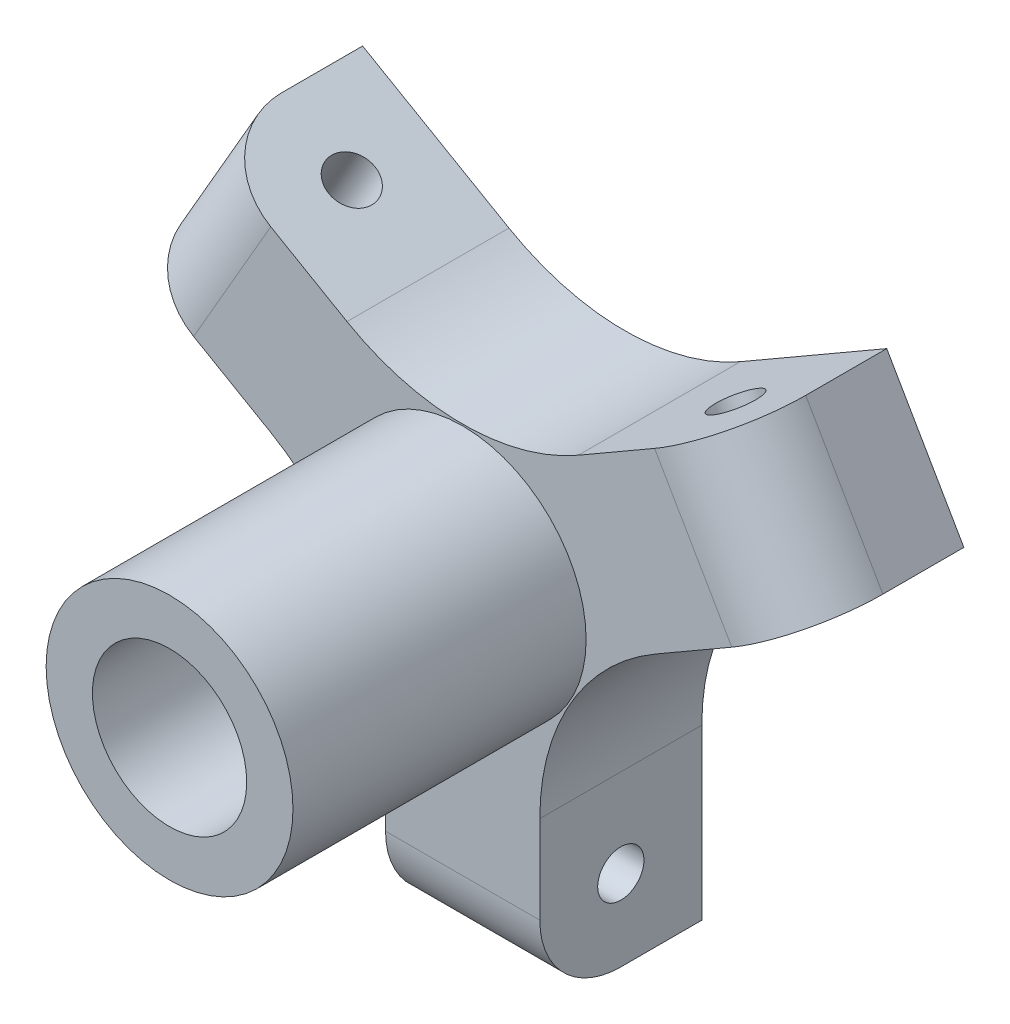
SolidWorks part; units mm, degrees
material "Hierro dúctil (SN)"
ref_plane "Alzado" through (0, 0, 0) normal (0, 0, 1) x (1, 0, 0)
ref_plane "Planta" through (0, 0, 0) normal (0, 1, 0) x (1, 0, 0)
ref_plane "Vista lateral" through (0, 0, 0) normal (1, 0, 0) x (0, 0, -1)
sketch "Croquis1" plane through (0, 0, 0) normal (0, 0, 1) x (1, 0, 0)
  line L0 (15, 20.2073) -> (33.9711, 31.1603)
  line L4 (33.9711, 31.1603) -> (43.9711, 13.8397)
  line L5 (43.9711, 13.8397) -> (25, 2.8868)
  line L6 (10, -23.094) -> (10, -45)
  line L7 (-10, -45) -> (-10, -23.094)
  line L8 (10, -45) -> (-10, -45)
  line L9 (-25, 2.8868) -> (-43.9711, 13.8397)
  line L10 (-33.9711, 31.1603) -> (-15, 20.2073)
  line L11 (-43.9711, 13.8397) -> (-33.9711, 31.1603)
  arc A2 (10, -23.094) -> (25, 2.8868) centre (40, -23.094) cw
  arc A3 (-10, -23.094) -> (-25, 2.8868) centre (-40, -23.094) ccw
  arc A4 (15, 20.2073) -> (-15, 20.2073) centre (0, 46.188) cw
  point P19 (0, 0)
  dimension "D4" = 30
  dimension "D1" = 20
  dimension "D3" = 3
extrude "Saliente-Extruir1" add sketch "Croquis1" along normal blind 21
fillet "Redondeo1" radius 10.5 3 edges at (-38.9711, 22.5, 21) (38.9711, 22.5, 21) (0, -45, 21)
sketch "Croquis2" plane through (0, 0, 21) normal (0, 0, 1) x (1, 0, 0)
  circle A0 centre (0, 0) radius 16
  dimension "D1" = 32
extrude "Saliente-Extruir2" add sketch "Croquis2" along normal blind 38
sketch "Croquis3" plane through (0, 0, 59) normal (0, 0, 1) x (1, 0, 0)
  circle A0 centre (0, 0) radius 10
  dimension "D1" = 20
extrude "Cortar-Extruir1" cut sketch "Croquis3" against normal blind 74
sketch "Croquis4" plane through (5, 8.6603, 0) normal (0.5, 0.866, 0) x (0.866, -0.5, 0)
  circle A0 centre (-34.5, -10.5) radius 3
  dimension "D1" = 6
extrude "Cortar-Extruir2" cut sketch "Croquis4" against normal blind 25
pattern_circular "MatrizC1" count 3 over 360 about axis through (0, 0, 59) along (0, 0, -1) of "Cortar-Extruir2"
